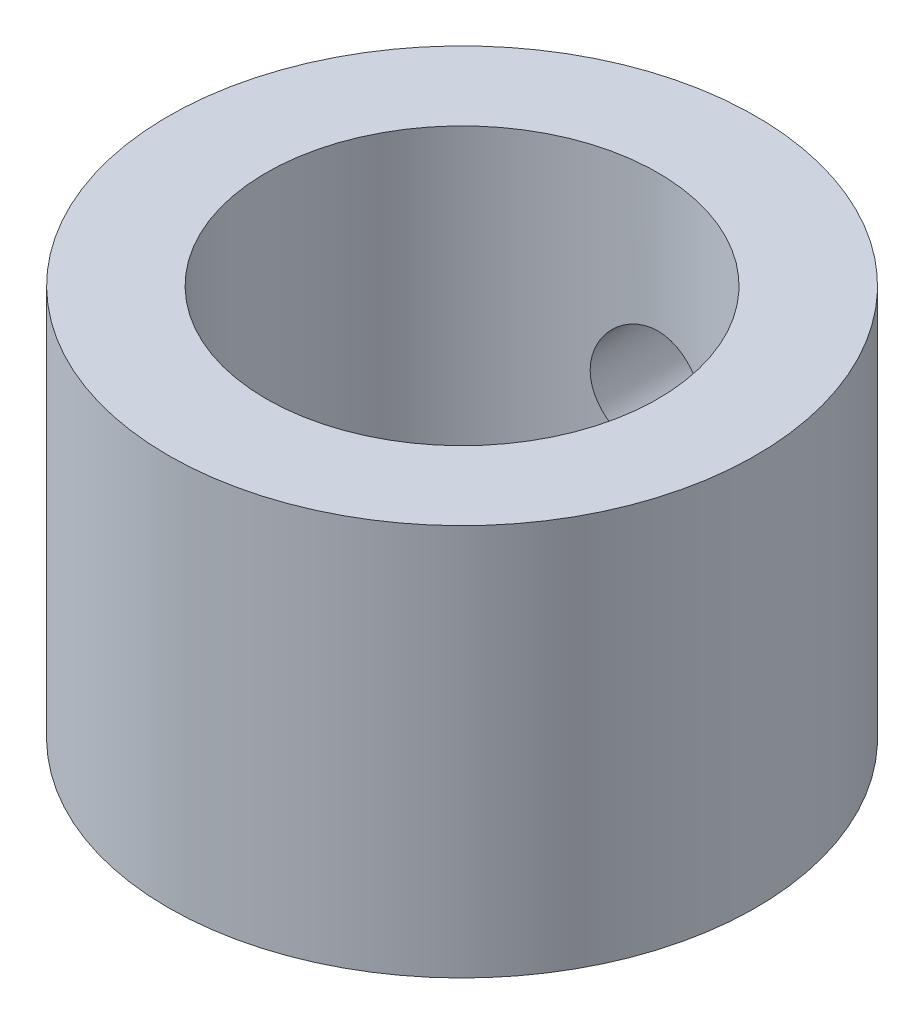
SolidWorks part; units mm, degrees
ref_plane "Front Plane" through (0, 0, 0) normal (0, 0, 1) x (1, 0, 0)
ref_plane "Top Plane" through (0, 0, 0) normal (0, 1, 0) x (1, 0, 0)
ref_plane "Right Plane" through (0, 0, 0) normal (1, 0, 0) x (0, 0, -1)
sketch "Sketch1" plane through (0, 0, 0) normal (0, 1, 0) x (1, 0, 0)
  circle A0 centre (0, 0) radius 7.5
  circle A1 centre (0, 0) radius 5
  dimension "D1" = 15
  dimension "D2" = 10
extrude "Boss-Extrude1" add sketch "Sketch1" along normal mid plane 10
sketch "Sketch2" plane through (0, 0, 0) normal (0, 0, 1) x (1, 0, 0)
  circle A1 centre (0, 0) radius 1.5
  dimension "D1" = 3
extrude "Cut-Extrude1" cut sketch "Sketch2" against normal up to surface (7.3485 mm away)
